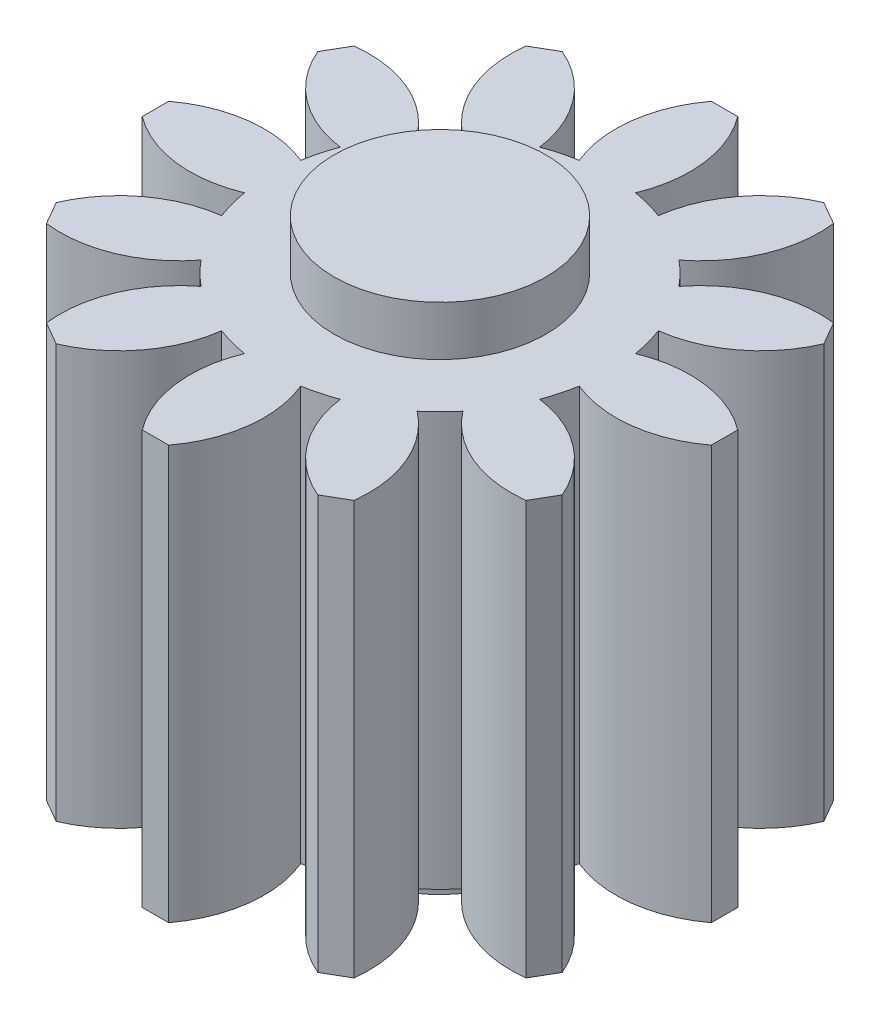
SolidWorks part; units mm, degrees
ref_plane "Front Plane" through (0, 0, 0) normal (0, 0, 1) x (1, 0, 0)
ref_plane "Top Plane" through (0, 0, 0) normal (0, 1, 0) x (1, 0, 0)
ref_plane "Right Plane" through (0, 0, 0) normal (1, 0, 0) x (0, 0, -1)
sketch "Sketch1" plane through (0, 0, 0) normal (1, 0, 0) x (0, 0, -1)
  line L0 (0, 0) -> (3.2, 0)
  line L1 (3.2, 0) -> (3.2, 1.5)
  line L2 (3.2, 1.5) -> (5.13, 1.5)
  line L3 (5.13, 1.5) -> (5.13, 14)
  line L4 (5.13, 14) -> (3.2, 14)
  line L5 (3.2, 14) -> (3.2, 15.5)
  line L6 (3.2, 15.5) -> (0, 15.5)
  line L7 (0, 15.5) -> (0, 0)
  dimension "D1" = 12.5
  dimension "D2" = 5.13
  dimension "D3" = 3.2
  dimension "D4" = 1.5
  dimension "D6" = 3.2
revolve "Revolve1" add sketch "Sketch1" angle 360 about L7
sketch "Sketch2" plane through (0, 14, 0) normal (0, 1, 0) x (1, 0, 0)
  line L0 (0, -5.6667) -> (0, 5.3655) construction
  line L1 (0, 5.3655) -> (0, 8.6) construction
  line L2 (0.4, 8.6) -> (-0.4, 8.6)
  line L3 (-0.85, 5.0591) -> (-0.85, 4.769)
  line L4 (-0.85, 4.769) -> (0.85, 4.769)
  line L5 (0.85, 4.769) -> (0.85, 5.0591)
  arc A0 (-0.4, 8.6) -> (-0.85, 5.0591) centre (2.4765, 6.4354) ccw
  circle A2 centre (0, 0) radius 5.13 construction
  arc A3 (0.4, 8.6) -> (0.85, 5.0591) centre (-2.4765, 6.4354) cw
  point P12 (0, 0)
  dimension "D2" = 3.6
  dimension "D1" = 0.4
  dimension "D3" = 1.7
  dimension "D4" = 8.6
extrude "Boss-Extrude2" add sketch "Sketch2" against normal blind 12.5
pattern_circular "CirPattern1" count 12 every 30 about axis through (0, 0, 0) along (0, 1, 0) of "Boss-Extrude2"
